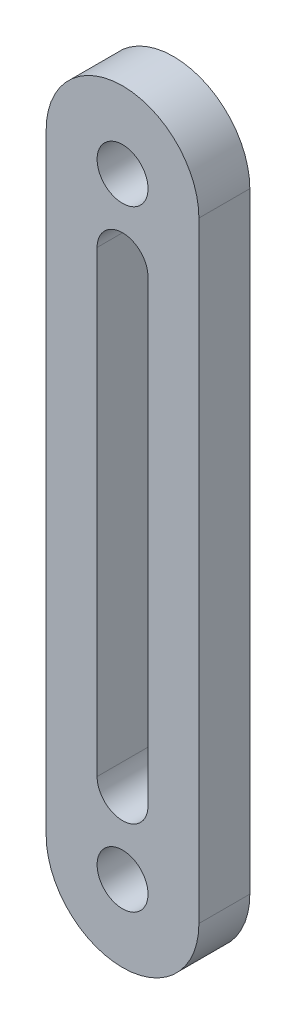
SolidWorks part; units mm, degrees
ref_plane "Alzado" through (0, 0, 0) normal (0, 0, 1) x (1, 0, 0)
ref_plane "Planta" through (0, 0, 0) normal (0, 1, 0) x (1, 0, 0)
ref_plane "Vista lateral" through (0, 0, 0) normal (1, 0, 0) x (0, 0, -1)
sketch "Model" plane through (0, 0, 0) normal (0, 0, 1) x (1, 0, 0)
  line L0 (213.2508, 152.4285) -> (213.2508, 188.4285)
  line L1 (204.2508, 188.4285) -> (204.2508, 152.4285)
  line L2 (207.2508, 183.9285) -> (207.2508, 156.9285)
  line L3 (210.2508, 156.9285) -> (210.2508, 183.9285)
  circle A0 centre (208.7508, 188.4285) radius 1.5
  circle A1 centre (208.7508, 152.4285) radius 1.5
  arc A2 (204.2508, 152.4285) -> (213.2508, 152.4285) centre (208.7508, 152.4285) ccw
  arc A3 (213.2508, 188.4285) -> (204.2508, 188.4285) centre (208.7508, 188.4285) ccw
  arc A4 (210.2508, 183.9285) -> (207.2508, 183.9285) centre (208.7508, 183.9285) ccw
  arc A5 (207.2508, 156.9285) -> (210.2508, 156.9285) centre (208.7508, 156.9285) ccw
extrude "Saliente-Extruir1" add sketch "Model" along normal blind 3
